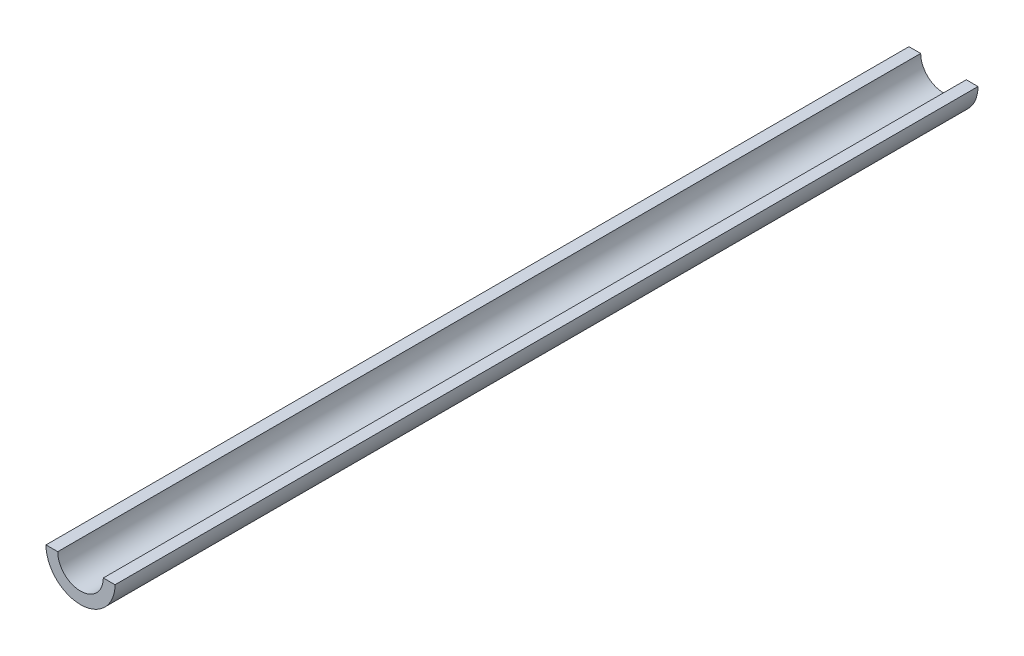
SolidWorks part; units mm, degrees
ref_plane "前视基准面" through (0, 0, 0) normal (0, 0, 1) x (1, 0, 0)
ref_plane "上视基准面" through (0, 0, 0) normal (0, 1, 0) x (1, 0, 0)
ref_plane "右视基准面" through (0, 0, 0) normal (1, 0, 0) x (0, 0, -1)
other "Configuration Table"
sketch "草图1" plane through (0, 0, 0) normal (0, 0, 1) x (1, 0, 0)
  line L0 (-10, 0) -> (-6.6, 0)
  line L1 (6.6, 0) -> (10, 0)
  arc A0 (-6.6, 0) -> (6.6, 0) centre (0, 0) ccw
  arc A1 (-10, 0) -> (10, 0) centre (0, 0) ccw
  dimension "D1" = 20
  dimension "D2" = 3.4
extrude "凸台-拉伸1" add sketch "草图1" along normal mid plane 250
